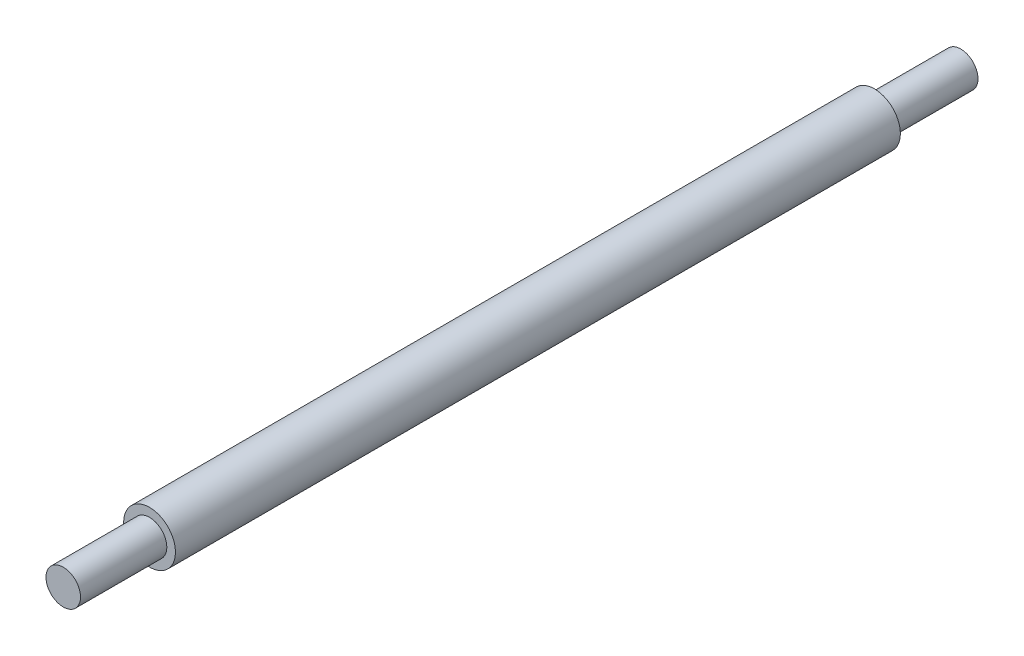
SolidWorks part; units mm, degrees
ref_plane "Front Plane" through (0, 0, 0) normal (0, 0, 1) x (1, 0, 0)
ref_plane "Top Plane" through (0, 0, 0) normal (0, 1, 0) x (1, 0, 0)
ref_plane "Right Plane" through (0, 0, 0) normal (1, 0, 0) x (0, 0, -1)
sketch "Sketch2" plane through (0, 0, 0) normal (1, 0, 0) x (0, 0, -1)
  line L0 (0, 0) -> (104, 0) construction
  line L1 (0, 0) -> (0, 2)
  line L2 (0, 2) -> (10, 2)
  line L3 (10, 2) -> (10, 3)
  line L4 (10, 3) -> (94, 3)
  line L5 (94, 3) -> (94, 2)
  line L6 (94, 2) -> (104, 2)
  line L7 (104, 2) -> (104, 0)
  line L8 (104, 0) -> (0, 0)
  point P3 (0, 1)
  dimension "D1" = 10
  dimension "D2" = 10
  dimension "D3" = 104
  dimension "D4" = 2
  dimension "D5" = 3
revolve "Revolve1" add sketch "Sketch2" angle 360 about L8
